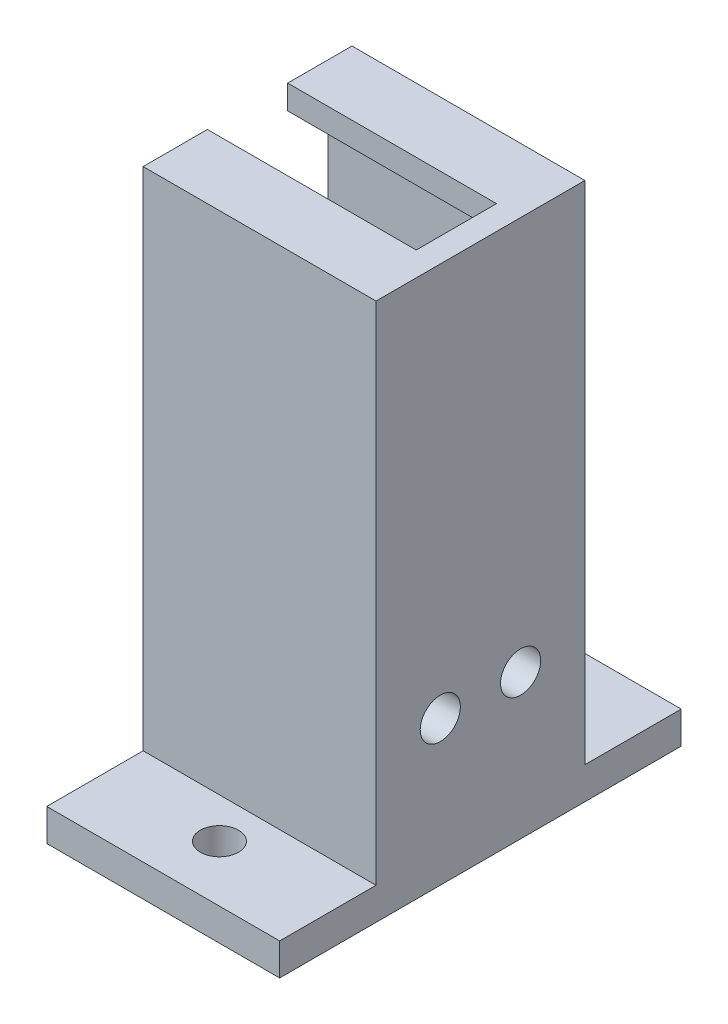
SolidWorks part; units mm, degrees
ref_plane "Front" through (0, 0, 0) normal (0, 0, 1) x (1, 0, 0)
ref_plane "Top" through (0, 0, 0) normal (0, 1, 0) x (1, 0, 0)
ref_plane "Right" through (0, 0, 0) normal (1, 0, 0) x (0, 0, -1)
sketch "Sketch1" plane through (0, 0, 0) normal (0, 0, 1) x (1, 0, 0)
  line L1 (0, 0) -> (29, 0)
  line L2 (0, 0) -> (0, 47)
  line L3 (0, 47) -> (29, 47)
  line L4 (29, 0) -> (29, 47)
  dimension "D1" = 29
  dimension "D2" = 47
extrude "Boss-Extrude1" add sketch "Sketch1" along normal blind 26
shell "Shell1" thickness 3
sketch "Sketch2" plane through (0, 0, 0) normal (-1, 0, 0) x (0, 0, 1)
  line L0 (23, 44) -> (3, 44) construction
  line L1 (8, 39.8846) -> (18, 39.8846)
  line L2 (8, 39.8846) -> (8, 48.1154)
  line L3 (8, 48.1154) -> (18, 48.1154)
  line L4 (18, 39.8846) -> (18, 48.1154)
  line L5 (8, 39.8846) -> (18, 48.1154) construction
  line L6 (8, 48.1154) -> (18, 39.8846) construction
  point P0 (13, 44)
  dimension "D1" = 10
extrude "Cut-Extrude1" cut sketch "Sketch2" against normal blind 26
sketch "Sketch3" plane through (0, 0, 0) normal (0, -1, 0) x (1, 0, 0)
  line L1 (0, 0) -> (29, 0)
  line L2 (0, 0) -> (0, 26)
  line L3 (0, 26) -> (29, 26)
  line L4 (29, 0) -> (29, 26)
extrude "Boss-Extrude2" add sketch "Sketch3" along normal blind 16
sketch "Sketch4" plane through (0, 0, 0) normal (-1, 0, 0) x (0, 0, 1)
  line L0 (8, -2) -> (18, -2) construction
  line L1 (18, -2) -> (26, -2) construction
  line L2 (26, 47) -> (26, -16) construction
  line L3 (8, -2) -> (0, -2) construction
  line L4 (0, 47) -> (0, -16) construction
  line L5 (18, -2) -> (18, 3) construction
  line L6 (23, 3) -> (3, 3) construction
  circle A0 centre (8, -2) radius 2.5
  circle A1 centre (18, -2) radius 2.5
  dimension "D1" = 5
  dimension "D2" = 5
  dimension "D3" = 10
  dimension "D4" = 5
extrude "Cut-Extrude2" cut sketch "Sketch4" against normal through all
sketch "Sketch5" plane through (0, -16, 0) normal (0, -1, 0) x (1, 0, 0)
  line L0 (0, 13) -> (29, 13) construction
  line L1 (0, 26) -> (0, 0) construction
  line L2 (29, 0) -> (29, 26) construction
  line L3 (14.5, 26) -> (14.5, 0) construction
  line L4 (29, 26) -> (0, 26) construction
  line L5 (0, 0) -> (29, 0) construction
  line L6 (14.5, 26) -> (14.5, 31) construction
  line L7 (0, -12) -> (29, -12)
  line L8 (0, -12) -> (0, 38)
  line L9 (0, 38) -> (29, 38)
  line L10 (29, -12) -> (29, 38)
  line L13 (14.5, 31) -> (14.5, 38) construction
  line L14 (14.5, 0) -> (14.5, -5) construction
  line L15 (14.5, -5) -> (14.5, -12) construction
  circle A0 centre (14.5, 31) radius 2.3812
  circle A1 centre (14.5, -5) radius 2.3813
  point P12 (14.5, 13)
  point P21 (0, 0)
  point P25 (0, 0)
  dimension "D2" = 4.7625
  dimension "D1" = 50
  dimension "D3" = 7
extrude "Boss-Extrude3" add sketch "Sketch5" along normal blind 4
